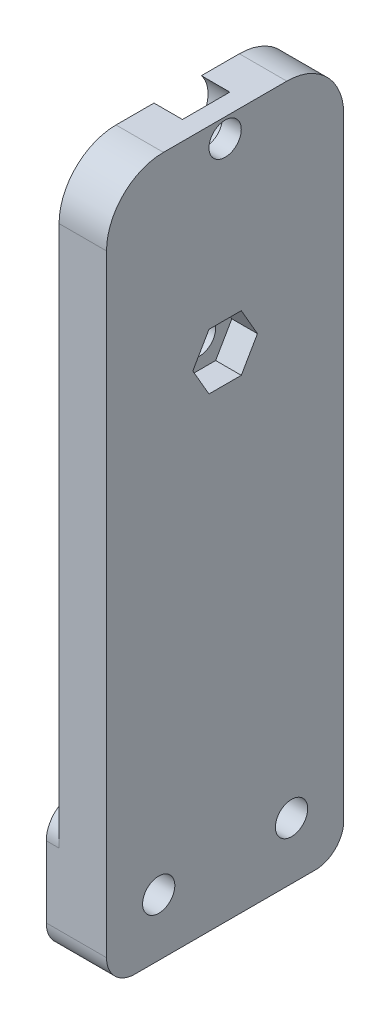
SolidWorks part; units mm, degrees
ref_plane "Front Plane" through (0, 0, 0) normal (0, 0, 1) x (1, 0, 0)
ref_plane "Top Plane" through (0, 0, 0) normal (0, 1, 0) x (1, 0, 0)
ref_plane "Right Plane" through (0, 0, 0) normal (1, 0, 0) x (0, 0, -1)
sketch "Sketch1" plane through (0, 0, 0) normal (1, 0, 0) x (0, 0, -1)
  line L0 (-1.5, 271.5) -> (-1.5, 336)
  line L1 (-7.5, 342) -> (-20.5, 342)
  line L2 (-26.5, 336) -> (-26.5, 271.5)
  line L3 (-23.5, 268.5) -> (-4.5, 268.5)
  arc A0 (-4.5, 268.5) -> (-1.5, 271.5) centre (-4.5, 271.5) ccw
  arc A1 (-1.5, 336) -> (-7.5, 342) centre (-7.5, 336) ccw
  arc A2 (-20.5, 342) -> (-26.5, 336) centre (-20.5, 336) ccw
  arc A3 (-26.5, 271.5) -> (-23.5, 268.5) centre (-23.5, 271.5) ccw
extrude "Cover plate" add sketch "Sketch1" along normal blind 5 from offset 26.9
sketch "Sketch2" plane through (0, 0, 0) normal (1, 0, 0) x (0, 0, -1)
  line L0 (-1.5, 271.5) -> (-1.5, 279)
  line L1 (-4.5, 282) -> (-23.5, 282)
  line L2 (-26.5, 279) -> (-26.5, 271.5)
  line L3 (-23.5, 268.5) -> (-4.5, 268.5)
  arc A0 (-4.5, 268.5) -> (-1.5, 271.5) centre (-4.5, 271.5) ccw
  arc A1 (-1.5, 279) -> (-4.5, 282) centre (-4.5, 279) ccw
  arc A2 (-23.5, 282) -> (-26.5, 279) centre (-23.5, 279) ccw
  arc A3 (-26.5, 271.5) -> (-23.5, 268.5) centre (-23.5, 271.5) ccw
extrude "Tail pad" add sketch "Sketch2" along normal blind 1.55 from offset 28.25
sketch "Sketch3" plane through (0, 0, 0) normal (1, 0, 0) x (0, 0, -1)
  circle A0 centre (-14, 320.5) radius 7.25
extrude "Pin seat" cut sketch "Sketch3" along normal blind 1.2 from offset 27.1
sketch "Sketch4" plane through (0, 0, 0) normal (1, 0, 0) x (0, 0, -1)
  circle A0 centre (-14, 320.5) radius 1.7
  circle A1 centre (-7, 274.5) radius 1.7
  circle A2 centre (-21, 274.5) radius 1.7
  circle A3 centre (-14, 340) radius 1.7
extrude "Bolt holes" cut sketch "Sketch4" along normal blind 6.85 from offset 28.55
sketch "Sketch5" plane through (0, 0, 0) normal (1, 0, 0) x (0, 0, -1)
  line L0 (-15.7032, 323.45) -> (-17.4064, 320.5)
  line L1 (-17.4064, 320.5) -> (-15.7032, 317.55)
  line L2 (-15.7032, 317.55) -> (-12.2968, 317.55)
  line L3 (-12.2968, 317.55) -> (-10.5936, 320.5)
  line L4 (-10.5936, 320.5) -> (-12.2968, 323.45)
  line L5 (-12.2968, 323.45) -> (-15.7032, 323.45)
extrude "Pin nut" cut sketch "Sketch5" along normal blind 2.9 from offset 24.6
sketch "Sketch6" plane through (0, 0, 0) normal (1, 0, 0) x (0, 0, -1)
  circle A0 centre (-14, 340) radius 3.2
extrude "Counterbore" cut sketch "Sketch6" along normal blind 3.2 from offset 27.1
